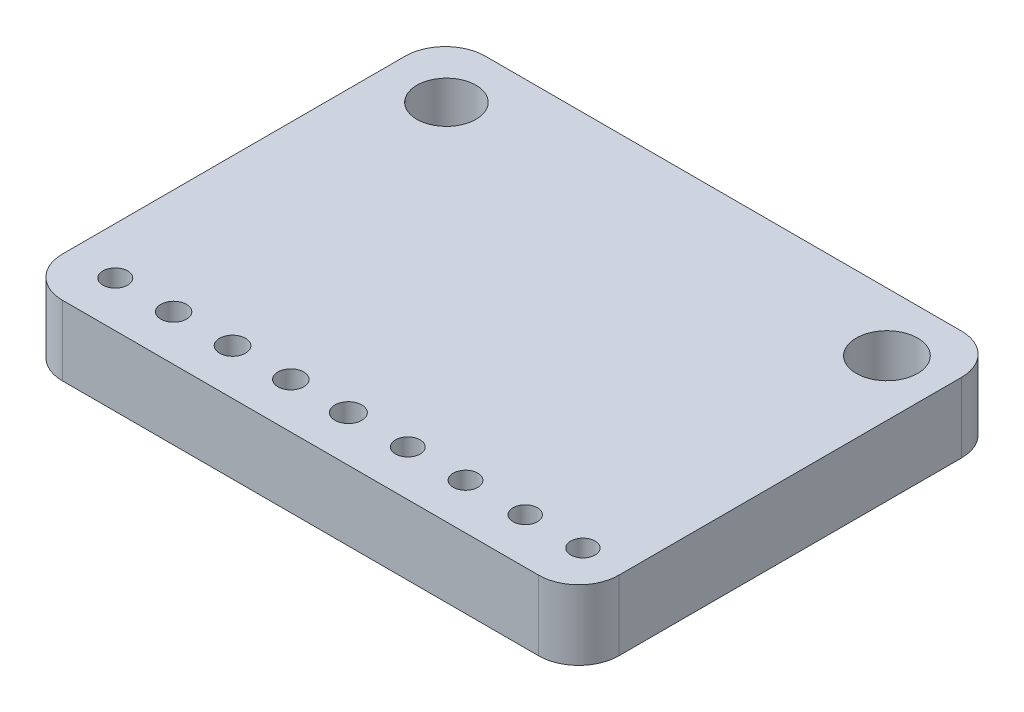
SolidWorks part; units mm, degrees
material "ABS PC"
ref_plane "Front Plane" through (0, 0, 0) normal (0, 0, 1) x (1, 0, 0)
ref_plane "Top Plane" through (0, 0, 0) normal (0, 1, 0) x (1, 0, 0)
ref_plane "Right Plane" through (0, 0, 0) normal (1, 0, 0) x (0, 0, -1)
sketch "Sketch1" plane through (0, 0, 0) normal (0, 1, 0) x (1, 0, 0)
  line L1 (0, 0) -> (25, 0)
  line L2 (0, 0) -> (0, 19)
  line L3 (0, 19) -> (25, 19)
  line L4 (25, 0) -> (25, 19)
  dimension "D1" = 19
  dimension "D2" = 25
extrude "Boss-Extrude1" add sketch "Sketch1" along normal blind 3.14
sketch "Sketch2" plane through (0, 3.14, 0) normal (0, 1, 0) x (1, 0, 0)
  circle A0 centre (2.7226, 16.3314) radius 1.3287
extrude "Cut-Extrude1" cut sketch "Sketch2" against normal through all
sketch "Sketch3" plane through (0, 3.14, 0) normal (0, 1, 0) x (1, 0, 0)
  circle A0 centre (22.4837, 16.3648) radius 1.3791
extrude "Cut-Extrude2" cut sketch "Sketch3" against normal through all
sketch "Sketch4" plane through (0, 3.14, 0) normal (0, 1, 0) x (1, 0, 0)
  circle A0 centre (23.1371, 2.0505) radius 0.5464
  circle A1 centre (20.5436, 2.0505) radius 0.5472
  circle A2 centre (17.8609, 2.0505) radius 0.5539
  circle A3 centre (15.2681, 2.0505) radius 0.5544
  circle A4 centre (12.5976, 2.0505) radius 0.6026
  circle A5 centre (10.01, 2.0505) radius 0.5806
  circle A6 centre (7.3904, 2.0505) radius 0.5831
  circle A7 centre (4.7448, 2.0505) radius 0.5782
  circle A8 centre (2.1214, 2.0505) radius 0.5566
extrude "Cut-Extrude3" cut sketch "Sketch4" against normal through all
fillet "Fillet1" radius 1.8 4 edges at (25, 1.57, 0) (0, 1.57, 0) (0, 1.57, -19) (25, 1.57, -19)
